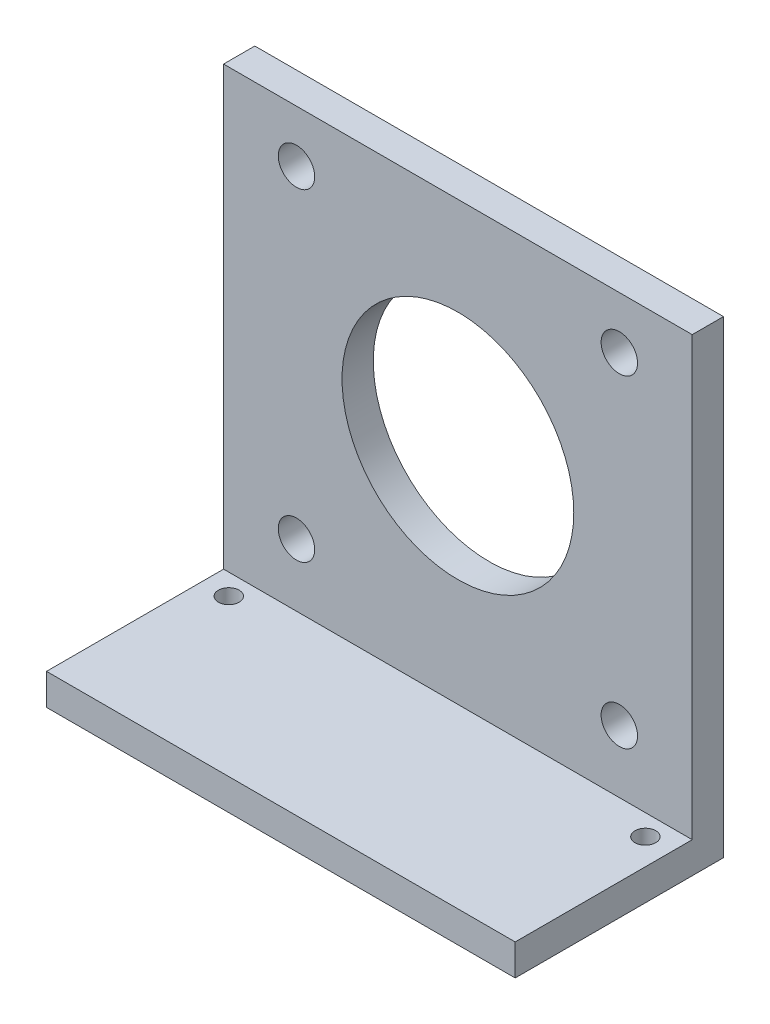
SolidWorks part; units mm, degrees
ref_plane "Plan de face" through (0, 0, 0) normal (0, 0, 1) x (1, 0, 0)
ref_plane "Plan de dessus" through (0, 0, 0) normal (0, 1, 0) x (1, 0, 0)
ref_plane "Plan de droite" through (0, 0, 0) normal (1, 0, 0) x (0, 0, -1)
sketch "Esquisse1" plane through (0, 0, 0) normal (0, 0, 1) x (1, 0, 0)
  line L0 (0, 31) -> (31, 0) construction
  line L1 (0, 31) -> (31, 31) construction
  line L2 (0, 31) -> (0, 0) construction
  line L3 (0, 0) -> (31, 0) construction
  line L4 (31, 31) -> (31, 0) construction
  line L5 (-7, 36) -> (38, 36)
  line L6 (-7, 36) -> (-7, -6)
  line L7 (-7, -6) -> (38, -6)
  line L8 (38, 36) -> (38, -6)
  circle A0 centre (0, 31) radius 1.75
  circle A1 centre (31, 31) radius 1.75
  circle A2 centre (31, 0) radius 1.75
  circle A3 centre (0, 0) radius 1.75
  circle A4 centre (15.5, 15.5) radius 11.125
  point P14 (0, 15.5)
  dimension "D5" = 3.5
  dimension "D6" = 22.25
  dimension "D1" = 5
  dimension "D2" = 7
  dimension "D3" = 6
  dimension "D4" = 31
  dimension "D7" = 7
extrude "Boss.-Extru.1" add sketch "Esquisse1" along normal blind 3
sketch "Esquisse3" plane through (0, -6, 0) normal (0, -1, 0) x (1, 0, 0)
  line L1 (-7, 0) -> (38, 0)
  line L2 (-7, 0) -> (-7, 20)
  line L3 (-7, 20) -> (38, 20)
  line L4 (38, 0) -> (38, 20)
  line L5 (-7, 3) -> (38, 3) construction
  line L6 (15.5, 20) -> (15.5, 3) construction
  circle A0 centre (-4.5, 5) radius 1
  circle A2 centre (35.5, 5) radius 1
  dimension "D2" = 2
  dimension "D3" = 15
  dimension "D1" = 20
  dimension "D4" = 20
extrude "Boss.-Extru.2" add sketch "Esquisse3" along normal blind 3
equation "\"D2@Esquisse1\"=\"D1@Esquisse1\""
